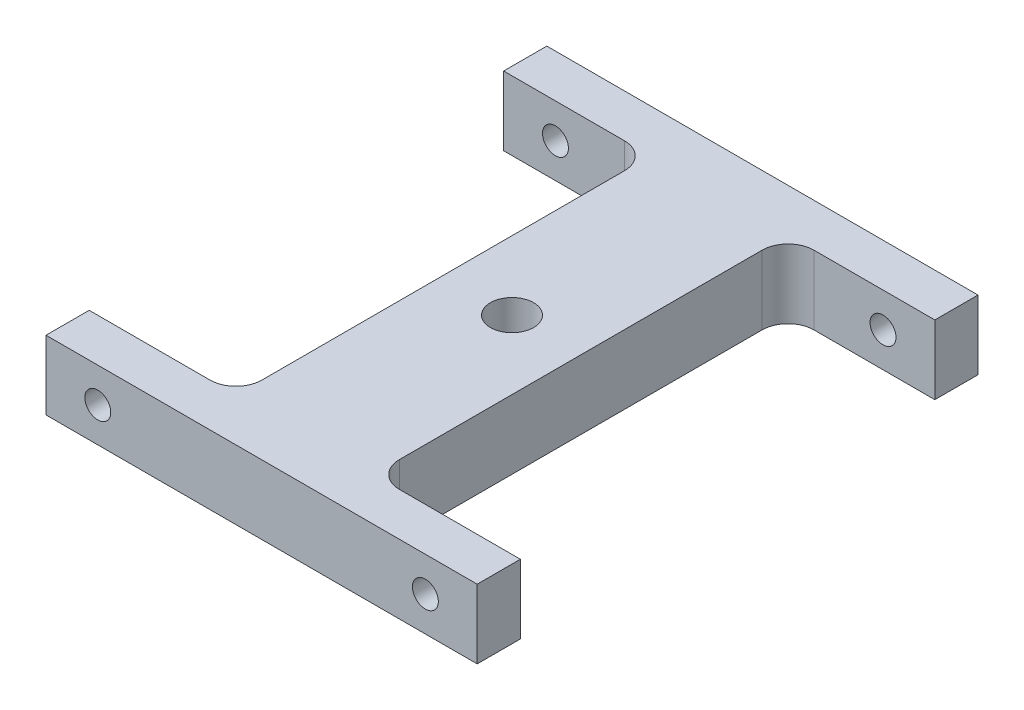
SolidWorks part; units mm, degrees
ref_plane "前视基准面" through (0, 0, 0) normal (0, 0, 1) x (1, 0, 0)
ref_plane "上视基准面" through (0, 0, 0) normal (0, 1, 0) x (1, 0, 0)
ref_plane "右视基准面" through (0, 0, 0) normal (1, 0, 0) x (0, 0, -1)
sketch "草图1" plane through (0, 0, 0) normal (0, 0, 1) x (1, 0, 0)
  line L0 (24.9678, -110) -> (24.9678, -5) construction
  line L1 (-24.9678, -110) -> (24.9678, -110)
  line L2 (-24.9678, -110) -> (-24.9678, -102)
  line L3 (-24.9678, -102) -> (24.9678, -102)
  line L4 (24.9678, -110) -> (24.9678, -102)
  dimension "D1" = 8
extrude "凸台-拉伸1" add sketch "草图1" along normal up to vertex (58 mm away)
sketch "草图2" plane through (0, -110, 0) normal (0, -1, 0) x (1, 0, 0)
  line L1 (-24.9678, 53) -> (-10.9678, 53)
  line L2 (-24.9678, 53) -> (-24.9678, 5)
  line L3 (-24.9678, 5) -> (-10.9678, 5)
  line L4 (-7.9678, 50) -> (-7.9678, 8)
  line L5 (24.9678, 5) -> (10.9678, 5)
  line L6 (24.9678, 5) -> (24.9678, 53)
  line L7 (24.9678, 53) -> (10.9678, 53)
  line L8 (7.9678, 8) -> (7.9678, 50)
  arc A0 (10.9678, 5) -> (7.9678, 8) centre (10.9678, 8) cw
  arc A1 (10.9678, 53) -> (7.9678, 50) centre (10.9678, 50) ccw
  arc A2 (-10.9678, 53) -> (-7.9678, 50) centre (-10.9678, 50) cw
  arc A3 (-10.9678, 5) -> (-7.9678, 8) centre (-10.9678, 8) ccw
  point P14 (7.9678, 53)
  point P17 (-7.9678, 53)
  dimension "D3" = 3
  dimension "D1" = 17
  dimension "D2" = 17
extrude "切除-拉伸1" cut sketch "草图2" against normal blind 56
sketch "草图3" plane through (0, -110, 0) normal (0, -1, 0) x (1, 0, 0)
  line L0 (-24.9678, 58) -> (24.9678, 0) construction
  line L1 (24.9678, 58) -> (-24.9678, 0) construction
  circle A0 centre (0, 29) radius 2.5
  dimension "D1" = 5
sketch "草图4" plane through (0, 0, 53) normal (0, 0, -1) x (-1, 0, 0)
  line L0 (24.9678, -106) -> (-24.9678, -106) construction
  line L1 (24.9678, -102) -> (24.9678, -110) construction
  line L2 (-24.9678, -102) -> (-24.9678, -110) construction
  circle A0 centre (18.9678, -106) radius 1.5
  circle A1 centre (-18.9678, -106) radius 1.5
  dimension "D1" = 3
  dimension "D2" = 3
  dimension "D3" = 6
  dimension "D4" = 6
extrude "切除-拉伸2" cut sketch "草图4" against normal blind 10 and the other way blind 66
extrude "切除-拉伸3" cut sketch "草图3" against normal blind 8
